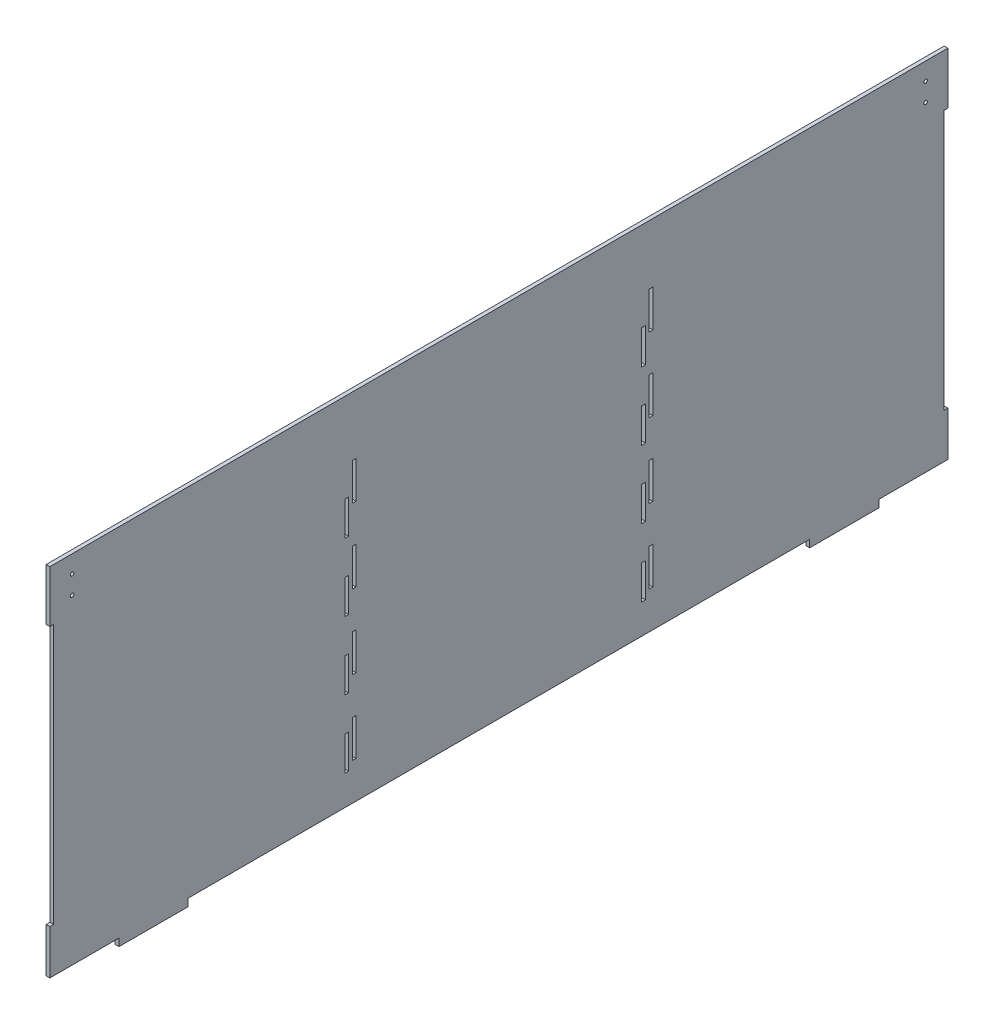
SolidWorks part; units mm, degrees
material "Acrylic (Medium-high impact)"
ref_plane "Front Plane" through (0, 0, 0) normal (0, 0, 1) x (1, 0, 0)
ref_plane "Top Plane" through (0, 0, 0) normal (0, 1, 0) x (1, 0, 0)
ref_plane "Right Plane" through (0, 0, 0) normal (1, 0, 0) x (0, 0, -1)
sketch "Sketch1" plane through (0, 0, 0) normal (1, 0, 0) x (0, 0, -1)
  line L0 (0, 152.4) -> (0, -152.4) construction
  line L1 (-381, 152.4) -> (381, 152.4)
  line L2 (-381, 152.4) -> (-381, -152.4)
  line L3 (-381, -152.4) -> (381, -152.4)
  line L4 (381, 152.4) -> (381, -152.4)
  line L5 (-381, 107.95) -> (-381, 63.5)
  line L10 (-381, 152.4) -> (-384.175, 152.4)
  line L11 (-381, 152.4) -> (-381, 107.95)
  line L12 (-381, 107.95) -> (-384.175, 107.95)
  line L13 (-384.175, 152.4) -> (-384.175, 107.95)
  line L14 (381, 152.4) -> (384.175, 152.4)
  line L15 (381, 152.4) -> (381, 107.95)
  line L16 (381, 107.95) -> (384.175, 107.95)
  line L17 (384.175, 152.4) -> (384.175, 107.95)
  line L18 (-384.175, -152.4) -> (-325.0712, -152.4)
  line L19 (-384.175, -152.4) -> (-384.175, -158.75)
  line L20 (-384.175, -158.75) -> (-325.0712, -158.75)
  line L21 (-325.0712, -152.4) -> (-325.0712, -158.75)
  line L22 (-381, 107.95) -> (-384.175, 107.95)
  line L23 (-384.175, 107.95) -> (-384.175, 63.5)
  line L24 (-381, 63.5) -> (-384.175, 63.5)
  line L25 (381, 107.95) -> (381, 63.5)
  line L26 (381, 107.95) -> (384.175, 107.95)
  line L27 (384.175, 107.95) -> (384.175, 63.5)
  line L28 (381, 63.5) -> (384.175, 63.5)
  line L29 (-381, 63.5) -> (-381, 19.05)
  line L30 (-381, 63.5) -> (-384.175, 63.5)
  line L31 (-384.175, 63.5) -> (-384.175, 19.05)
  line L32 (-381, 19.05) -> (-384.175, 19.05)
  line L33 (381, 63.5) -> (381, 19.05)
  line L34 (381, 63.5) -> (384.175, 63.5)
  line L35 (384.175, 63.5) -> (384.175, 19.05)
  line L36 (381, 19.05) -> (384.175, 19.05)
  line L37 (-381, 19.05) -> (-381, -25.4)
  line L38 (-381, 19.05) -> (-384.175, 19.05)
  line L39 (-384.175, 19.05) -> (-384.175, -25.4)
  line L40 (-381, -25.4) -> (-384.175, -25.4)
  line L41 (381, 19.05) -> (381, -25.4)
  line L42 (381, 19.05) -> (384.175, 19.05)
  line L43 (384.175, 19.05) -> (384.175, -25.4)
  line L44 (381, -25.4) -> (384.175, -25.4)
  line L45 (-381, -25.4) -> (-381, -69.85)
  line L46 (-381, -25.4) -> (-384.175, -25.4)
  line L47 (-384.175, -25.4) -> (-384.175, -69.85)
  line L48 (-381, -69.85) -> (-384.175, -69.85)
  line L49 (381, -25.4) -> (381, -69.85)
  line L50 (381, -25.4) -> (384.175, -25.4)
  line L51 (384.175, -25.4) -> (384.175, -69.85)
  line L52 (381, -69.85) -> (384.175, -69.85)
  line L53 (-381, -69.85) -> (-381, -114.3)
  line L54 (-381, -69.85) -> (-384.175, -69.85)
  line L55 (-384.175, -69.85) -> (-384.175, -114.3)
  line L56 (-381, -114.3) -> (-384.175, -114.3)
  line L57 (381, -69.85) -> (381, -114.3)
  line L58 (381, -69.85) -> (384.175, -69.85)
  line L59 (384.175, -69.85) -> (384.175, -114.3)
  line L60 (381, -114.3) -> (384.175, -114.3)
  line L61 (-381, -114.3) -> (-381, -158.75)
  line L62 (-381, -114.3) -> (-384.175, -114.3)
  line L63 (-384.175, -114.3) -> (-384.175, -158.75)
  line L64 (-381, -158.75) -> (-384.175, -158.75)
  line L65 (381, -114.3) -> (381, -158.75)
  line L66 (381, -114.3) -> (384.175, -114.3)
  line L67 (384.175, -114.3) -> (384.175, -158.75)
  line L68 (381, -158.75) -> (384.175, -158.75)
  line L69 (-325.0712, -158.75) -> (-265.9673, -158.75)
  line L70 (-325.0712, -152.4) -> (-325.0712, -158.75)
  line L71 (-325.0712, -152.4) -> (-265.9673, -152.4)
  line L72 (-265.9673, -152.4) -> (-265.9673, -158.75)
  line L73 (-265.9673, -158.75) -> (-206.8635, -158.75)
  line L74 (-265.9673, -152.4) -> (-265.9673, -158.75)
  line L75 (-265.9673, -152.4) -> (-206.8635, -152.4)
  line L76 (-206.8635, -152.4) -> (-206.8635, -158.75)
  line L77 (-206.8635, -158.75) -> (-147.7596, -158.75)
  line L78 (-206.8635, -152.4) -> (-206.8635, -158.75)
  line L79 (-206.8635, -152.4) -> (-147.7596, -152.4)
  line L80 (-147.7596, -152.4) -> (-147.7596, -158.75)
  line L81 (-147.7596, -158.75) -> (-88.6558, -158.75)
  line L82 (-147.7596, -152.4) -> (-147.7596, -158.75)
  line L83 (-147.7596, -152.4) -> (-88.6558, -152.4)
  line L84 (-88.6558, -152.4) -> (-88.6558, -158.75)
  line L85 (-88.6558, -158.75) -> (-29.5519, -158.75)
  line L86 (-88.6558, -152.4) -> (-88.6558, -158.75)
  line L87 (-88.6558, -152.4) -> (-29.5519, -152.4)
  line L88 (-29.5519, -152.4) -> (-29.5519, -158.75)
  line L89 (-29.5519, -158.75) -> (29.5519, -158.75)
  line L90 (-29.5519, -152.4) -> (-29.5519, -158.75)
  line L91 (-29.5519, -152.4) -> (29.5519, -152.4)
  line L92 (29.5519, -152.4) -> (29.5519, -158.75)
  line L93 (29.5519, -158.75) -> (88.6558, -158.75)
  line L94 (29.5519, -152.4) -> (29.5519, -158.75)
  line L95 (29.5519, -152.4) -> (88.6558, -152.4)
  line L96 (88.6558, -152.4) -> (88.6558, -158.75)
  line L97 (88.6558, -158.75) -> (147.7596, -158.75)
  line L98 (88.6558, -152.4) -> (88.6558, -158.75)
  line L99 (88.6558, -152.4) -> (147.7596, -152.4)
  line L100 (147.7596, -152.4) -> (147.7596, -158.75)
  line L101 (147.7596, -158.75) -> (206.8635, -158.75)
  line L102 (147.7596, -152.4) -> (147.7596, -158.75)
  line L103 (147.7596, -152.4) -> (206.8635, -152.4)
  line L104 (206.8635, -152.4) -> (206.8635, -158.75)
  line L105 (206.8635, -158.75) -> (265.9673, -158.75)
  line L106 (206.8635, -152.4) -> (206.8635, -158.75)
  line L107 (206.8635, -152.4) -> (265.9673, -152.4)
  line L108 (265.9673, -152.4) -> (265.9673, -158.75)
  line L125 (-125.4125, 0) -> (125.4125, 0) construction
  line L126 (-128.5875, 41.956) -> (-125.4125, 41.956) construction
  line L127 (-128.5875, 41.956) -> (-128.5875, -41.956) construction
  line L128 (-128.5875, -41.956) -> (-125.4125, -41.956) construction
  line L129 (-125.4125, 41.956) -> (-125.4125, -41.956) construction
  line L138 (125.4125, 41.956) -> (128.5875, 41.956) construction
  line L139 (125.4125, 41.956) -> (125.4125, -41.956) construction
  line L140 (125.4125, -41.956) -> (128.5875, -41.956) construction
  line L141 (128.5875, 41.956) -> (128.5875, -41.956) construction
  line L143 (265.9673, -158.75) -> (325.0712, -158.75)
  line L144 (265.9673, -152.4) -> (265.9673, -158.75)
  line L145 (265.9673, -152.4) -> (325.0712, -152.4)
  line L146 (325.0712, -152.4) -> (325.0712, -158.75)
  line L147 (325.0712, -158.75) -> (384.175, -158.75)
  line L148 (325.0712, -152.4) -> (325.0712, -158.75)
  line L149 (325.0712, -152.4) -> (384.175, -152.4)
  line L150 (384.175, -152.4) -> (384.175, -158.75)
  point P6 (0, 0)
  point P113 (-127, 41.956)
  point P114 (127, 41.956)
  point P117 (0, 0)
  dimension "D1" = 762
  dimension "D2" = 304.8
  dimension "D3" = 768.35
  dimension "D4" = 311.15
  dimension "D5" = 44.45
  dimension "D7" = 59.1038
  dimension "D9" = 254
  dimension "D10" = 3.175
  dimension "D6" = 7
  dimension "D8" = 13
extrude "Boss-Extrude1" add sketch "Sketch1" along normal blind 3.175
sketch "Sketch3" plane through (3.175, 0, 0) normal (1, 0, 0) x (0, 0, -1)
  line L0 (-128.5887, -127) -> (-128.5887, 76.2) construction
  line L5 (-131.7637, 76.2) -> (-128.5887, 76.2)
  line L6 (-131.7637, 76.2) -> (-131.7637, 47.1714)
  line L7 (-131.7637, 47.1714) -> (-128.5887, 47.1714)
  line L8 (-128.5887, 76.2) -> (-128.5887, 47.1714)
  line L9 (-122.2363, 101.6) -> (-125.4113, 101.6)
  line L10 (-122.2363, 101.6) -> (-122.2363, 69.85)
  line L11 (-122.2363, 69.85) -> (-125.4113, 69.85)
  line L12 (-125.4113, 101.6) -> (-125.4113, 69.85)
  line L13 (-381, -152.4) -> (381, -152.4) construction
  line L14 (-125.4113, -152.4) -> (-125.4113, 101.6) construction
  line L15 (-128.5887, 76.2) -> (-125.4113, 76.2) construction
  line L16 (-127, 41.956) -> (-127, 76.2) construction
  line L17 (-128.5875, 41.956) -> (-125.4125, 41.956) construction
  line L18 (-122.2363, 69.85) -> (-122.2363, 38.1)
  line L19 (-122.2363, 69.85) -> (-125.4113, 69.85)
  line L20 (-125.4113, 69.85) -> (-125.4113, 38.1)
  line L21 (-122.2363, 38.1) -> (-125.4113, 38.1)
  line L22 (-122.2363, 38.1) -> (-122.2363, 6.35)
  line L23 (-122.2363, 38.1) -> (-125.4113, 38.1)
  line L24 (-125.4113, 38.1) -> (-125.4113, 6.35)
  line L25 (-122.2363, 6.35) -> (-125.4113, 6.35)
  line L26 (-122.2363, 6.35) -> (-122.2363, -25.4)
  line L27 (-122.2363, 6.35) -> (-125.4113, 6.35)
  line L28 (-125.4113, 6.35) -> (-125.4113, -25.4)
  line L29 (-122.2363, -25.4) -> (-125.4113, -25.4)
  line L30 (-122.2363, -25.4) -> (-122.2363, -57.15)
  line L31 (-122.2363, -25.4) -> (-125.4113, -25.4)
  line L32 (-125.4113, -25.4) -> (-125.4113, -57.15)
  line L33 (-122.2363, -57.15) -> (-125.4113, -57.15)
  line L34 (-122.2363, -57.15) -> (-122.2363, -88.9)
  line L35 (-122.2363, -57.15) -> (-125.4113, -57.15)
  line L36 (-125.4113, -57.15) -> (-125.4113, -88.9)
  line L37 (-122.2363, -88.9) -> (-125.4113, -88.9)
  line L38 (-122.2363, -88.9) -> (-122.2363, -120.65)
  line L39 (-122.2363, -88.9) -> (-125.4113, -88.9)
  line L40 (-125.4113, -88.9) -> (-125.4113, -120.65)
  line L41 (-122.2363, -120.65) -> (-125.4113, -120.65)
  line L42 (-131.7637, 47.1714) -> (-131.7637, 18.1429)
  line L43 (-131.7637, 47.1714) -> (-128.5887, 47.1714)
  line L44 (-128.5887, 47.1714) -> (-128.5887, 18.1429)
  line L45 (-131.7637, 18.1429) -> (-128.5887, 18.1429)
  line L46 (-131.7637, 18.1429) -> (-131.7637, -10.8857)
  line L47 (-131.7637, 18.1429) -> (-128.5887, 18.1429)
  line L48 (-128.5887, 18.1429) -> (-128.5887, -10.8857)
  line L49 (-131.7637, -10.8857) -> (-128.5887, -10.8857)
  line L50 (-131.7637, -10.8857) -> (-131.7637, -39.9143)
  line L51 (-131.7637, -10.8857) -> (-128.5887, -10.8857)
  line L52 (-128.5887, -10.8857) -> (-128.5887, -39.9143)
  line L53 (-131.7637, -39.9143) -> (-128.5887, -39.9143)
  line L54 (-131.7637, -39.9143) -> (-131.7637, -68.9429)
  line L55 (-131.7637, -39.9143) -> (-128.5887, -39.9143)
  line L56 (-128.5887, -39.9143) -> (-128.5887, -68.9429)
  line L57 (-131.7637, -68.9429) -> (-128.5887, -68.9429)
  line L58 (-131.7637, -68.9429) -> (-131.7637, -97.9714)
  line L59 (-131.7637, -68.9429) -> (-128.5887, -68.9429)
  line L60 (-128.5887, -68.9429) -> (-128.5887, -97.9714)
  line L61 (-131.7637, -97.9714) -> (-128.5887, -97.9714)
  line L62 (-131.7637, -97.9714) -> (-131.7637, -127)
  line L63 (-131.7637, -97.9714) -> (-128.5887, -97.9714)
  line L64 (-128.5887, -97.9714) -> (-128.5887, -127)
  line L65 (-131.7637, -127) -> (-128.5887, -127)
  line L66 (-122.2363, -120.65) -> (-122.2363, -152.4)
  line L67 (-122.2363, -120.65) -> (-125.4113, -120.65)
  line L68 (-125.4113, -120.65) -> (-125.4113, -152.4)
  line L69 (-122.2363, -152.4) -> (-125.4113, -152.4)
  line L70 (122.2363, 76.2) -> (125.4113, 76.2)
  line L71 (122.2363, 76.2) -> (122.2363, 47.1714)
  line L72 (122.2363, 47.1714) -> (125.4113, 47.1714)
  line L73 (125.4113, 76.2) -> (125.4113, 47.1714)
  line L74 (131.7637, 101.6) -> (128.5887, 101.6)
  line L75 (131.7637, 101.6) -> (131.7637, 69.85)
  line L76 (131.7637, 69.85) -> (128.5887, 69.85)
  line L77 (128.5887, 101.6) -> (128.5887, 69.85)
  line L78 (131.7637, 69.85) -> (131.7637, 38.1)
  line L79 (131.7637, 69.85) -> (128.5887, 69.85)
  line L80 (128.5887, 69.85) -> (128.5887, 38.1)
  line L81 (131.7637, 38.1) -> (128.5887, 38.1)
  line L82 (131.7637, 38.1) -> (131.7637, 6.35)
  line L83 (131.7637, 38.1) -> (128.5887, 38.1)
  line L84 (128.5887, 38.1) -> (128.5887, 6.35)
  line L85 (131.7637, 6.35) -> (128.5887, 6.35)
  line L86 (131.7637, 6.35) -> (131.7637, -25.4)
  line L87 (131.7637, 6.35) -> (128.5887, 6.35)
  line L88 (128.5887, 6.35) -> (128.5887, -25.4)
  line L89 (131.7637, -25.4) -> (128.5887, -25.4)
  line L90 (131.7637, -25.4) -> (131.7637, -57.15)
  line L91 (131.7637, -25.4) -> (128.5887, -25.4)
  line L92 (128.5887, -25.4) -> (128.5887, -57.15)
  line L93 (131.7637, -57.15) -> (128.5887, -57.15)
  line L94 (131.7637, -57.15) -> (131.7637, -88.9)
  line L95 (131.7637, -57.15) -> (128.5887, -57.15)
  line L96 (128.5887, -57.15) -> (128.5887, -88.9)
  line L97 (131.7637, -88.9) -> (128.5887, -88.9)
  line L98 (131.7637, -88.9) -> (131.7637, -120.65)
  line L99 (131.7637, -88.9) -> (128.5887, -88.9)
  line L100 (128.5887, -88.9) -> (128.5887, -120.65)
  line L101 (131.7637, -120.65) -> (128.5887, -120.65)
  line L102 (122.2363, 47.1714) -> (122.2363, 18.1429)
  line L103 (122.2363, 47.1714) -> (125.4113, 47.1714)
  line L104 (125.4113, 47.1714) -> (125.4113, 18.1429)
  line L105 (122.2363, 18.1429) -> (125.4113, 18.1429)
  line L106 (122.2363, 18.1429) -> (122.2363, -10.8857)
  line L107 (122.2363, 18.1429) -> (125.4113, 18.1429)
  line L108 (125.4113, 18.1429) -> (125.4113, -10.8857)
  line L109 (122.2363, -10.8857) -> (125.4113, -10.8857)
  line L110 (122.2363, -10.8857) -> (122.2363, -39.9143)
  line L111 (122.2363, -10.8857) -> (125.4113, -10.8857)
  line L112 (125.4113, -10.8857) -> (125.4113, -39.9143)
  line L113 (122.2363, -39.9143) -> (125.4113, -39.9143)
  line L114 (122.2363, -39.9143) -> (122.2363, -68.9429)
  line L115 (122.2363, -39.9143) -> (125.4113, -39.9143)
  line L116 (125.4113, -39.9143) -> (125.4113, -68.9429)
  line L117 (122.2363, -68.9429) -> (125.4113, -68.9429)
  line L118 (122.2363, -68.9429) -> (122.2363, -97.9714)
  line L119 (122.2363, -68.9429) -> (125.4113, -68.9429)
  line L120 (125.4113, -68.9429) -> (125.4113, -97.9714)
  line L121 (122.2363, -97.9714) -> (125.4113, -97.9714)
  line L122 (122.2363, -97.9714) -> (122.2363, -127)
  line L123 (122.2363, -97.9714) -> (125.4113, -97.9714)
  line L124 (125.4113, -97.9714) -> (125.4113, -127)
  line L125 (122.2363, -127) -> (125.4113, -127)
  line L126 (131.7637, -120.65) -> (131.7637, -152.4)
  line L127 (131.7637, -120.65) -> (128.5887, -120.65)
  line L128 (128.5887, -120.65) -> (128.5887, -152.4)
  line L129 (131.7637, -152.4) -> (128.5887, -152.4)
  line L130 (125.4113, -127) -> (125.4113, 76.2) construction
  line L131 (128.5887, -152.4) -> (128.5887, 101.6) construction
  line L132 (125.4113, 76.2) -> (128.5887, 76.2) construction
  line L133 (127, 41.956) -> (127, 76.2) construction
  line L134 (125.4125, 41.956) -> (128.5875, 41.956) construction
  dimension "D1" = 203.2
  dimension "D2" = 254
  dimension "D3" = 25.4
  dimension "D4" = 3.1775
  dimension "D5" = 3.175
  dimension "D7" = 31.75
  dimension "D9" = 29.0286
  dimension "D6" = 8
  dimension "D8" = 7
  dimension "D10" = 2
extrude "Cut-Extrude1" cut sketch "Sketch3" against normal through all contours L41 L38 L37 L40 | L33 L30 L29 L32 | L25 L22 L21 L24 | L9 L12 L11 L10 | L8 L5 L6 L7 | L46 L49 L48 L45 | L54 L57 L56 L53 | L62 L65 L64 L61 | L74 L77 L76 L75 | L73 L70 L71 L72 | L85 L82 L81 L84 | L106 L109 L108 L105 | L93 L90 L89 L92 | L114 L117 L116 L113 | L101 L98 L97 L100 | L122 L125 L124 L121
sketch "Sketch4" plane through (3.175, 0, 0) normal (1, 0, 0) x (0, 0, -1)
  line L0 (0, 152.4) -> (0, -152.4) construction
  line L1 (-384.175, 152.4) -> (384.175, 152.4) construction
  line L5 (-384.175, 152.4) -> (-384.175, 107.95) construction
  circle A0 centre (-365.125, 137.4) radius 1.5
  circle A1 centre (-365.125, 121.65) radius 1.5
  circle A2 centre (365.125, 137.4) radius 1.5
  circle A3 centre (365.125, 121.65) radius 1.5
  dimension "D1" = 3
  dimension "D2" = 3
  dimension "D3" = 19.05
  dimension "D4" = 15.75
  dimension "D5" = 15
extrude "Cut-Extrude2" cut sketch "Sketch4" against normal up to surface (3.175 mm away) up to face at (0, 3.6286, 130.1762)
sketch "Sketch5" plane through (3.175, 0, 0) normal (1, 0, 0) x (0, 0, -1)
  line L0 (-384.175, 63.5) -> (-381, 63.5)
  line L1 (-381, 63.5) -> (-381, 19.05)
  line L2 (-381, 19.05) -> (-384.175, 19.05)
  line L3 (-384.175, 19.05) -> (-384.175, 63.5)
  line L4 (-384.175, -25.4) -> (-381, -25.4)
  line L5 (-381, -25.4) -> (-381, -69.85)
  line L6 (-381, -69.85) -> (-384.175, -69.85)
  line L7 (-384.175, -69.85) -> (-384.175, -25.4)
  line L9 (-206.8635, -152.4) -> (-147.7596, -152.4)
  line L10 (-206.8635, -152.4) -> (-206.8635, -158.75)
  line L11 (-206.8635, -158.75) -> (-147.7596, -158.75)
  line L12 (-147.7596, -152.4) -> (-147.7596, -158.75)
  line L13 (-88.6558, -152.4) -> (-29.5519, -152.4)
  line L14 (-88.6558, -152.4) -> (-88.6558, -158.75)
  line L15 (-88.6558, -158.75) -> (-29.5519, -158.75)
  line L16 (-29.5519, -152.4) -> (-29.5519, -158.75)
  line L17 (29.5519, -152.4) -> (88.6558, -152.4)
  line L18 (29.5519, -152.4) -> (29.5519, -158.75)
  line L19 (29.5519, -158.75) -> (88.6558, -158.75)
  line L20 (88.6558, -152.4) -> (88.6558, -158.75)
  line L21 (147.7596, -152.4) -> (206.8635, -152.4)
  line L22 (147.7596, -152.4) -> (147.7596, -158.75)
  line L23 (147.7596, -158.75) -> (206.8635, -158.75)
  line L24 (206.8635, -152.4) -> (206.8635, -158.75)
  line L25 (384.175, -69.85) -> (381, -69.85)
  line L26 (384.175, -69.85) -> (384.175, -25.4)
  line L27 (384.175, -25.4) -> (381, -25.4)
  line L28 (381, -69.85) -> (381, -25.4)
  line L29 (384.175, 19.05) -> (381, 19.05)
  line L30 (384.175, 19.05) -> (384.175, 63.5)
  line L31 (384.175, 63.5) -> (381, 63.5)
  line L32 (381, 19.05) -> (381, 63.5)
extrude "Cut-Extrude3" cut sketch "Sketch5" against normal up to surface (3.175 mm away) up to face at (0, 121.65, 363.625)
equation "\"Height\"= 12in"
equation "\"Depth\"= 7in"
equation "\"WallThickness\"= 0.125in"
equation "\"FloorThickness\"= 0.25in"
equation "\"D2@Sketch1\"=\"Height\""
equation "\"D3@Sketch1\"=\"D1@Sketch1\"+2*\"WallThickness\""
equation "\"D4@Sketch1\"=\"D2@Sketch1\"+\"FloorThickness\""
equation "\"D5@Sketch1\"=\"D4@Sketch1\"/7"
equation "\"D7@Sketch1\"=\"D3@Sketch1\"/\"D8@Sketch1\""
equation "\"D1@Boss-Extrude1\"=\"WallThickness\""
equation "\"Width\" = 30in"
equation "\"D4@Sketch3\"=\"WallThickness\"+(1/16in)"
equation "\"D5@Sketch3\"=\"WallThickness\""
equation "\"D7@Sketch3\"=\"D2@Sketch3\"/\"D6@Sketch3\""
equation "\"D9@Sketch3\"=\"D1@Sketch3\"/\"D8@Sketch3\""
equation "\"D10@Sketch1\"=\"WallThickness\""
equation "\"D1@Sketch1\"=\"Width\""
